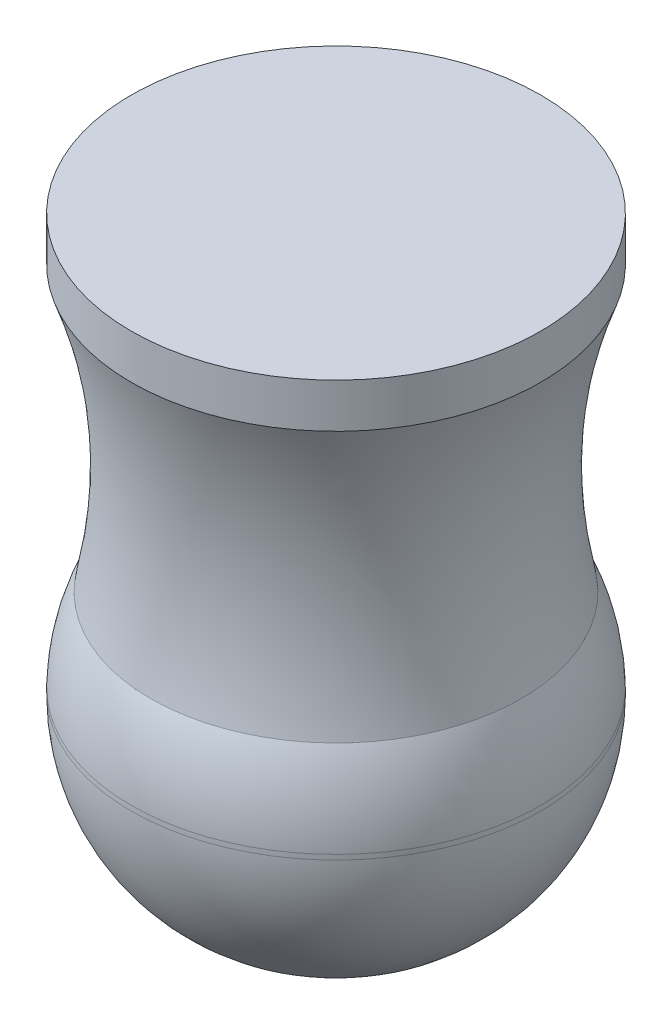
SolidWorks part; units mm, degrees
ref_plane "前视基准面" through (0, 0, 0) normal (0, 0, 1) x (1, 0, 0)
ref_plane "上视基准面" through (0, 0, 0) normal (0, 1, 0) x (1, 0, 0)
ref_plane "右视基准面" through (0, 0, 0) normal (1, 0, 0) x (0, 0, -1)
other "Configuration Table"
ref_plane "基准面3" through (0, -1.4, 0) normal (0, 1, 0) x (1, 0, 0)
sketch "草图2" plane through (0, -1.4, 0) normal (0, 1, 0) x (1, 0, 0)
  circle A0 centre (0, 0) radius 3.0037
extrude "凸台-拉伸1" add sketch "草图2" along normal blind 9
fillet "圆角1" radius 2.9 1 edges at (0, -1.4, 3.0037)
sketch "草图3" plane through (0, 0, 0) normal (1, 0, 0) x (0, 0, -1)
  line L2 (3.0044, 1.5087) -> (3.0044, 6.9512)
  arc A1 (3.0044, 1.5087) -> (2.7187, 2.7863) centre (0.0044, 1.5087) ccw
  spline S0 degree 2 poles (3.0044, 6.9512) (2.2688, 4.9432) (2.7187, 2.7863) knots 0 0 0 1 1 1
revolve "切除-旋转2" cut sketch "草图3" angle 360 about axis through (0, 7.6, 0) along (0, -1, 0)
